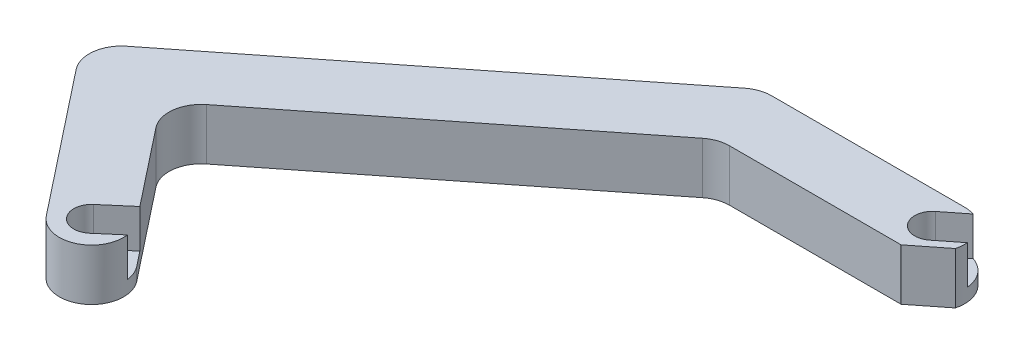
SolidWorks part; units mm, degrees
ref_plane "Front Plane" through (0, 0, 0) normal (0, 0, 1) x (1, 0, 0)
ref_plane "Top Plane" through (0, 0, 0) normal (0, 1, 0) x (1, 0, 0)
ref_plane "Right Plane" through (0, 0, 0) normal (1, 0, 0) x (0, 0, -1)
sketch "Sketch1" plane through (0, 0, 0) normal (0, 1, 0) x (1, 0, 0)
  line L0 (-7.7125, 6.5) -> (22.2875, 6.5)
  line L1 (-7.7125, -3.5) -> (22.2875, -3.5)
  arc A0 (-7.7125, 6.5) -> (-7.7125, -3.5) centre (-7.7125, 1.5) ccw
  arc A1 (22.2875, -3.5) -> (22.2875, 6.5) centre (22.2875, 1.5) ccw
  circle A2 centre (-7.7125, 1.5) radius 2.75 construction
  circle A3 centre (22.2875, 1.5) radius 2.75
  dimension "D3" = 5.5
  dimension "D4" = 5.5
  dimension "D5" = 5
  dimension "D2" = 30
extrude "Boss-Extrude1" add sketch "Sketch1" along normal blind 8
sketch "Sketch2" plane through (0, 8, 0) normal (0, 1, 0) x (1, 0, 0)
  line L0 (7.2875, 6.5) -> (7.2875, -6.8516) construction
  line L5 (22.2875, 6.5) -> (-7.7125, 6.5) construction
  line L10 (22.2875, 1.5) -> (-7.7125, 1.5) construction
  line L11 (20.5835, 3.6584) -> (23.9915, -0.6584)
  line L12 (20.5835, 3.6584) -> (30.5143, 11.4986)
  line L13 (23.9915, -0.6584) -> (33.9223, 7.1817)
  line L14 (30.5143, 11.4986) -> (33.9223, 7.1817)
  line L15 (27.2875, 1.5) -> (27.9244, 1.5) construction
  circle A1 centre (22.2875, 1.5) radius 2.75 construction
  arc A2 (22.2875, -3.5) -> (22.2875, 6.5) centre (22.2875, 1.5) ccw construction
  dimension "D2" = 12.6527
  dimension "D3" = 38.29
extrude "Cut-Extrude1" cut sketch "Sketch2" against normal blind 6
sketch "Sketch3" plane through (0, 8, 0) normal (0, 1, 0) x (1, 0, 0)
  line L0 (19.6071, -5.7124) -> (21.8689, -8.5774)
  line L1 (19.6071, -5.7124) -> (31.8186, 3.9283)
  line L2 (21.8689, -8.5774) -> (34.0804, 1.0633)
  line L3 (31.8186, 3.9283) -> (34.0804, 1.0633)
  line L4 (23.9915, -0.6584) -> (27.269, 1.9291) construction
  arc A0 (20.5835, 3.6584) -> (23.9915, -0.6584) centre (22.2875, 1.5) ccw construction
  dimension "D1" = 3.6501
  dimension "D2" = 4
  dimension "D3" = 15.5584
  dimension "D4" = 6.5729
extrude "Cut-Extrude2" cut sketch "Sketch3" against normal through all
sketch "Sketch4" plane through (0, 8, 0) normal (0, 1, 0) x (1, 0, 0)
  line L0 (-4.6143, -2.4244) -> (-54.3366, -41.6789)
  line L1 (-10.8107, 5.4244) -> (-64.4575, -36.9283)
  line L2 (23.861, 6.246) -> (20.5835, 3.6584) construction
  line L3 (23.9915, -0.6584) -> (27.269, 1.9291) construction
  line L4 (-7.7125, 1.5) -> (-61.3593, -40.8527) construction
  line L5 (23.9915, -0.6584) -> (27.269, 1.9291) construction
  line L6 (-7.7125, 1.5) -> (-17.3631, 13.724) construction
  line L7 (-7.7125, 1.5) -> (-1.128, -6.8404) construction
  line L8 (-65.2837, -43.9509) -> (-47.8903, -65.9826)
  line L9 (-69.5783, -30.4419) -> (-43.9658, -62.8843) construction
  line L10 (-61.3593, -40.8527) -> (-78.5479, -54.4227) construction
  line L11 (-54.0297, -70.8295) -> (-31.9636, -53.4089) construction
  line L12 (-40.0414, -59.7861) -> (-54.3366, -41.6789)
  arc A0 (-4.6143, -2.4244) -> (-10.8107, 5.4244) centre (-7.7125, 1.5) ccw
  arc A1 (-64.4575, -36.9283) -> (-65.2837, -43.9509) centre (-61.3593, -40.8527) ccw
  arc A2 (-47.8903, -65.9826) -> (-40.0414, -59.7861) centre (-43.9658, -62.8843) ccw
  circle A3 centre (-43.9658, -62.8843) radius 2.75
  dimension "D1" = 28.07
  dimension "D3" = 5
  dimension "D4" = 5.5
  dimension "D2" = 68.35
extrude "Boss-Extrude2" add sketch "Sketch4" against normal up to surface (8 mm away) up to face at (12.538, 0, -0.6517)
sketch "Sketch5" plane through (0, 8, 0) normal (0, 1, 0) x (1, 0, 0)
  line L0 (-45.7547, -60.7957) -> (-42.177, -64.973)
  line L1 (-45.7547, -60.7957) -> (-36.2958, -52.6944)
  line L2 (-42.177, -64.973) -> (-32.7181, -56.8717)
  line L3 (-36.2958, -52.6944) -> (-32.7181, -56.8717)
  line L5 (-40.2024, -67.2784) -> (-47.2163, -59.0891) construction
  circle A0 centre (-43.9658, -62.8843) radius 2.75 construction
  point P6 (0, 0)
  point P8 (0, 0)
  dimension "D1" = 5.5
  dimension "D2" = 12.454
  dimension "D3" = 8.5819
extrude "Cut-Extrude3" cut sketch "Sketch5" against normal blind 6
fillet "Fillet1" radius 5 2 edges at (-5.9767, 4, 3.5) (-54.3366, 4, 41.6789)
